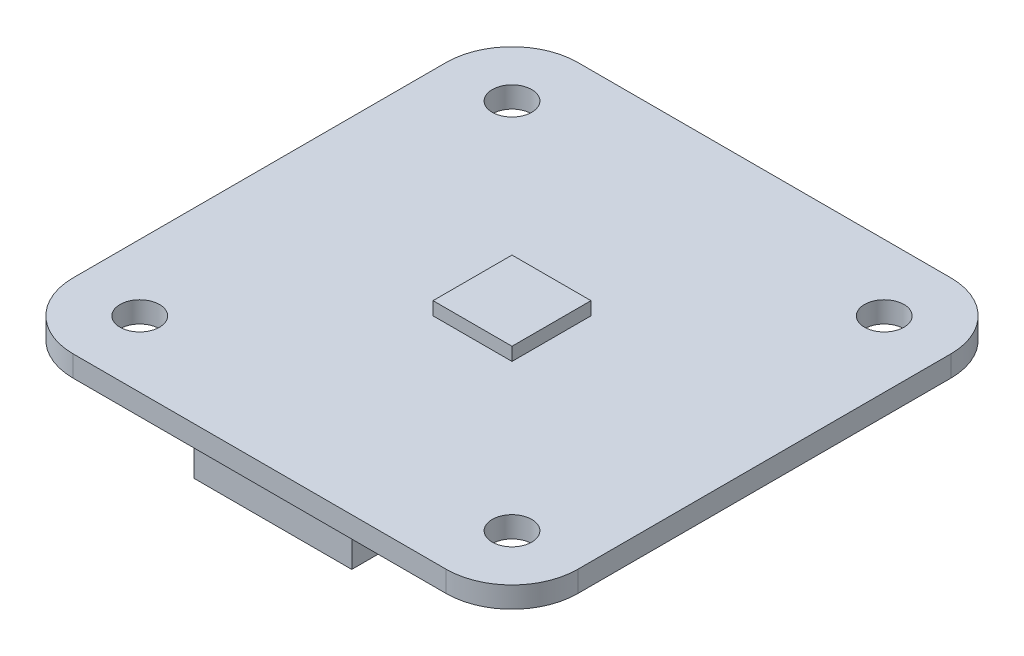
SolidWorks part; units mm, degrees
ref_plane "Front Plane" through (0, 0, 0) normal (0, 0, 1) x (1, 0, 0)
ref_plane "Top Plane" through (0, 0, 0) normal (0, 1, 0) x (1, 0, 0)
ref_plane "Right Plane" through (0, 0, 0) normal (1, 0, 0) x (0, 0, -1)
sketch "Sketch1" plane through (0, 0, 0) normal (0, 1, 0) x (1, 0, 0)
  line L1 (-19.175, 19.175) -> (19.175, 19.175)
  line L2 (-19.175, 19.175) -> (-19.175, -19.175)
  line L3 (-19.175, -19.175) -> (19.175, -19.175)
  line L4 (19.175, 19.175) -> (19.175, -19.175)
  line L5 (-19.175, 19.175) -> (19.175, -19.175) construction
  line L6 (-19.175, -19.175) -> (19.175, 19.175) construction
  point P0 (0, 0)
  dimension "D1" = 38.35
extrude "Boss-Extrude1" add sketch "Sketch1" along normal blind 1.6
fillet "Fillet1" radius 5 4 edges at (-19.175, 0.8, -19.175) (-19.175, 0.8, 19.175) (19.175, 0.8, -19.175) (19.175, 0.8, 19.175)
sketch "Sketch2" plane through (0, 1.6, 0) normal (0, 1, 0) x (1, 0, 0)
  line L0 (0, 0) -> (0, 19.175) construction
  line L1 (14.175, 19.175) -> (-14.175, 19.175) construction
  line L2 (0, 0) -> (-17.7105, 17.7105) construction
  arc A0 (-14.175, 19.175) -> (-19.175, 14.175) centre (-14.175, 14.175) ccw construction
  circle A1 centre (-14.1421, 14.1421) radius 1.5
  circle A2 centre (14.1421, 14.1421) radius 1.5
  circle A3 centre (-14.1421, -14.1421) radius 1.5
  circle A4 centre (14.1421, -14.1421) radius 1.5
  dimension "D2" = 3
  dimension "D3" = 20
  dimension "D1" = 45
  dimension "D4" = 20
extrude "Cut-Extrude1" cut sketch "Sketch2" against normal blind 1.6
sketch "Sketch3" plane through (0, 1.6, 0) normal (0, 1, 0) x (1, 0, 0)
  line L1 (-3, 3) -> (3, 3)
  line L2 (-3, 3) -> (-3, -3)
  line L3 (-3, -3) -> (3, -3)
  line L4 (3, 3) -> (3, -3)
  line L5 (-3, 3) -> (3, -3) construction
  line L6 (-3, -3) -> (3, 3) construction
  point P0 (0, 0)
  point P6 (0, 0)
  dimension "D1" = 6
extrude "Boss-Extrude2" add sketch "Sketch3" along normal blind 1
sketch "Sketch4" plane through (0, 0, 0) normal (0, -1, 0) x (1, 0, 0)
  line L0 (-14.175, 19.175) -> (14.175, 19.175) construction
  line L1 (-6, 18.175) -> (6, 18.175)
  line L2 (-6, 18.175) -> (-6, 10.175)
  line L3 (-6, 10.175) -> (6, 10.175)
  line L4 (6, 18.175) -> (6, 10.175)
  line L5 (-6, 18.175) -> (6, 10.175) construction
  line L6 (-6, 10.175) -> (6, 18.175) construction
  point P0 (0, 14.175)
  dimension "D1" = 12
  dimension "D2" = 8
  dimension "D3" = 1
extrude "Boss-Extrude3" add sketch "Sketch4" along normal blind 3
